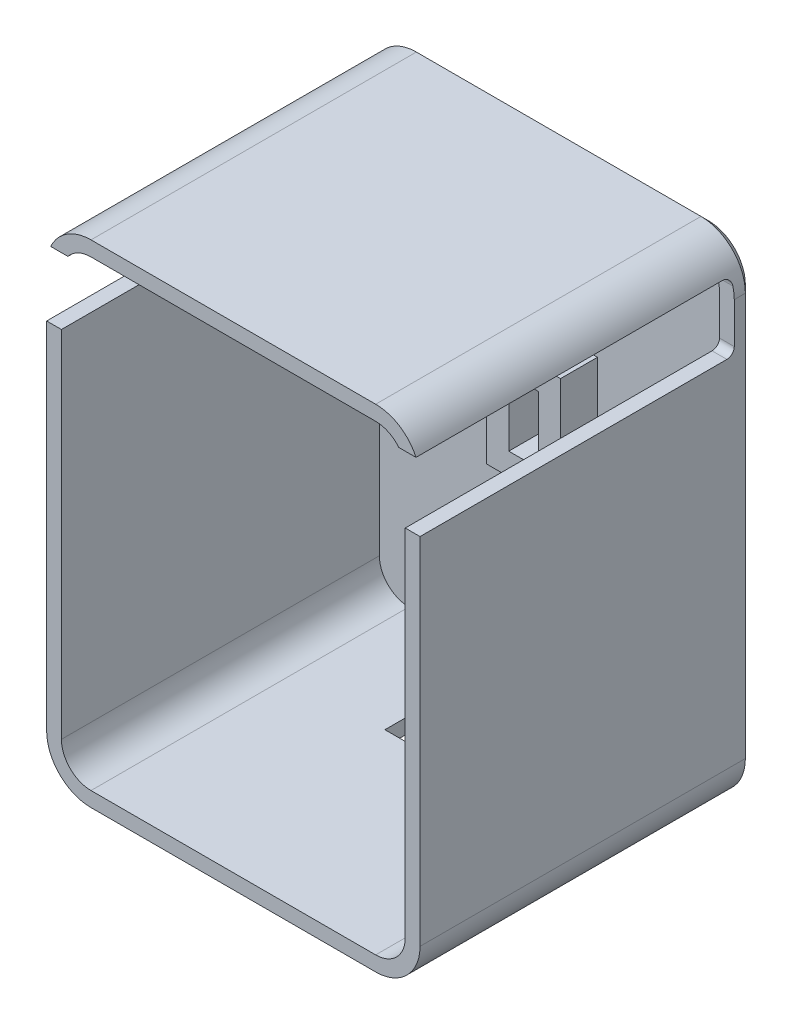
SolidWorks part; units mm, degrees
ref_plane "Plan de face" through (0, 0, 0) normal (0, 0, 1) x (1, 0, 0)
ref_plane "Plan de dessus" through (0, 0, 0) normal (0, 1, 0) x (1, 0, 0)
ref_plane "Plan de droite" through (0, 0, 0) normal (1, 0, 0) x (0, 0, -1)
sketch "Esquisse1" plane through (0, 0, 0) normal (0, 0, 1) x (1, 0, 0)
  line L1 (6, 0) -> (44.5, 0)
  line L2 (0, 6) -> (0, 60.5)
  line L3 (6, 66.5) -> (44.5, 66.5)
  line L4 (50.5, 6) -> (50.5, 60.5)
  arc A0 (44.5, 0) -> (50.5, 6) centre (44.5, 6) ccw
  arc A1 (0, 6) -> (6, 0) centre (6, 6) ccw
  arc A2 (0, 60.5) -> (6, 66.5) centre (6, 60.5) cw
  arc A3 (50.5, 60.5) -> (44.5, 66.5) centre (44.5, 60.5) ccw
  point P7 (50.5, 0)
  point P10 (0, 0)
  point P15 (50.5, 66.5)
  dimension "D3" = 6
  dimension "D1" = 50.5
  dimension "D2" = 66.5
extrude "Boss.-Extru.1" add sketch "Esquisse1" along normal blind 45
sketch "Esquisse3" plane through (0, 0, 45) normal (0, 0, 1) x (1, 0, 0)
  line L8 (2, 60.5) -> (2, 6)
  line L9 (6, 2) -> (44.5, 2)
  line L10 (48.5, 6) -> (48.5, 60.5)
  line L11 (44.5, 64.5) -> (6, 64.5)
  line L12 (2, 60.5) -> (2, 6)
  line L13 (6, 2) -> (44.5, 2)
  line L14 (48.5, 6) -> (48.5, 60.5)
  line L15 (44.5, 64.5) -> (6, 64.5)
  arc A4 (44.5, 2) -> (48.5, 6) centre (44.5, 6) ccw
  arc A5 (44.5, 2) -> (48.5, 6) centre (44.5, 6) ccw
  arc A6 (48.5, 60.5) -> (44.5, 64.5) centre (44.5, 60.5) ccw
  arc A7 (48.5, 60.5) -> (44.5, 64.5) centre (44.5, 60.5) ccw
  arc A8 (6, 64.5) -> (2, 60.5) centre (6, 60.5) ccw
  arc A9 (6, 64.5) -> (2, 60.5) centre (6, 60.5) ccw
  arc A10 (2, 6) -> (6, 2) centre (6, 6) ccw
  arc A11 (2, 6) -> (6, 2) centre (6, 6) ccw
  dimension "D1" = 2
extrude "Enlèv. mat.-Extru.1" cut sketch "Esquisse3" against normal blind 43
sketch "Esquisse4" plane through (50.5, 0, 0) normal (1, 0, 0) x (0, 0, -1)
  line L0 (-45, 66.5) -> (0, 66.5) construction
  line L1 (-57.9738, 63) -> (-3.5, 63)
  line L2 (-57.9738, 63) -> (-57.9738, 54)
  line L3 (-57.9738, 54) -> (-3.5, 54)
  line L4 (-2.5, 62) -> (-2.5, 55)
  line L9 (-45, 6) -> (-45, 60.5) construction
  arc A0 (-2.5, 62) -> (-3.5, 63) centre (-3.5, 62) ccw
  arc A1 (-3.5, 54) -> (-2.5, 55) centre (-3.5, 55) ccw
  dimension "D4" = 1
  dimension "D1" = 9
  dimension "D2" = 12.5
  dimension "D3" = 42.5
extrude "Enlèv. mat.-Extru.2" cut sketch "Esquisse4" against normal through all
chamfer "Chanfrein1" distance 1 angle 45 8 edges at (50.5, 33.25, 0) (48.7426, 64.7426, 0) (25.25, 66.5, 0) (1.7574, 64.7426, 0) (0, 33.25, 0) (1.7574, 1.7574, 0) (25.25, 0, 0) (48.7426, 1.7574, 0)
sketch "Esquisse6" plane through (0, 0, 2) normal (0, 0, 1) x (1, 0, 0)
  line L0 (2, 54) -> (2, 6) construction
  line L1 (21.5, 44) -> (31.5, 44)
  line L2 (21.5, 44) -> (21.5, 29)
  line L3 (21.5, 29) -> (31.5, 29)
  line L4 (31.5, 44) -> (31.5, 29)
  line L5 (24.5, 41) -> (28.5, 41)
  line L6 (44.5, 64.5) -> (6, 64.5) construction
  line L7 (28.5, 41) -> (28.5, 32)
  line L8 (24.5, 32) -> (28.5, 32)
  line L9 (24.5, 41) -> (24.5, 32)
  dimension "D1" = 10
  dimension "D2" = 15
  dimension "D3" = 19.5
  dimension "D4" = 20.5
  dimension "D5" = 3
extrude "Boss.-Extru.2" add sketch "Esquisse6" along normal blind 5
sketch "Esquisse8" plane through (0, 0, 0) normal (0, -1, 0) x (1, 0, 0)
  line L0 (0, 45) -> (0, 1) construction
  line L1 (18.75, 10) -> (29.75, 10)
  line L2 (18.75, 10) -> (18.75, 18)
  line L3 (18.75, 18) -> (29.75, 18)
  line L4 (29.75, 10) -> (29.75, 18)
  line L5 (44.5, 0) -> (6, 0) construction
  dimension "D1" = 11
  dimension "D2" = 8
  dimension "D3" = 18.75
  dimension "D4" = 10
extrude "Enlèv. mat.-Extru.5" cut sketch "Esquisse8" against normal blind 10
